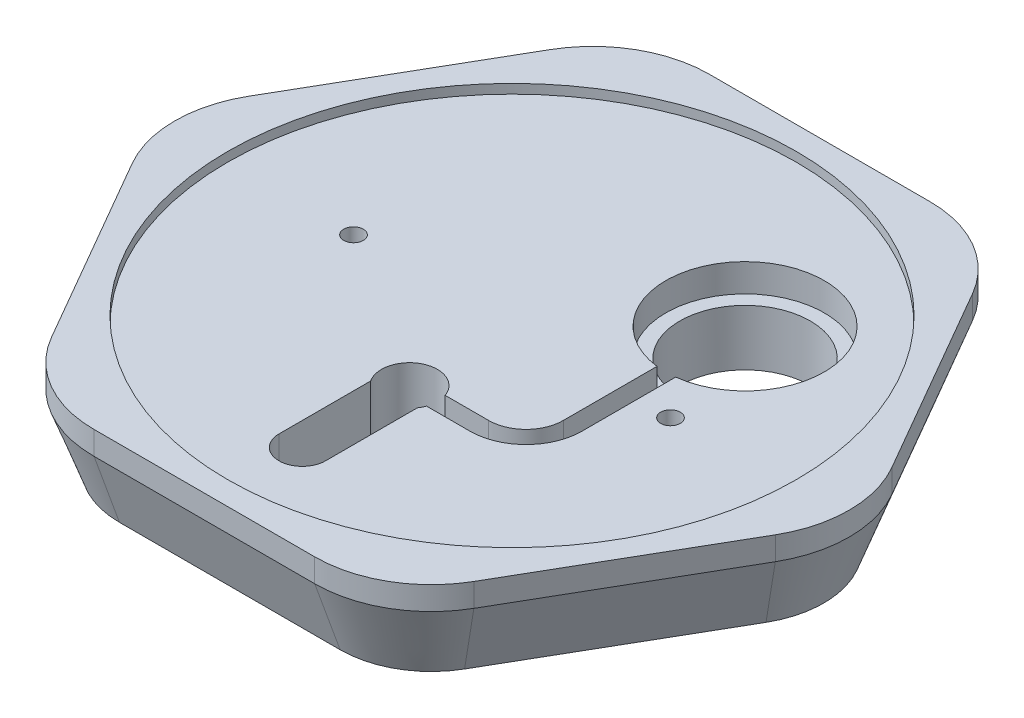
SolidWorks part; units mm, degrees
ref_plane "Front Plane" through (0, 0, 0) normal (0, 0, 1) x (1, 0, 0)
ref_plane "Top Plane" through (0, 0, 0) normal (0, 1, 0) x (1, 0, 0)
ref_plane "Right Plane" through (0, 0, 0) normal (1, 0, 0) x (0, 0, -1)
sketch "Sketch1" plane through (0, 0, 0) normal (0, 1, 0) x (1, 0, 0)
  line L1 (68.9934, 12.5) -> (45.322, 53.5)
  line L2 (23.6714, 66) -> (-23.6714, 66)
  line L3 (-45.322, 53.5) -> (-68.9934, 12.5)
  line L4 (-68.9934, -12.5) -> (-45.322, -53.5)
  line L5 (-23.6714, -66) -> (23.6714, -66)
  line L6 (45.322, -53.5) -> (68.9934, -12.5)
  circle A0 centre (0, 0) radius 66 construction
  arc A1 (-68.9934, 12.5) -> (-68.9934, -12.5) centre (-47.3427, 0) ccw
  arc A2 (-45.322, -53.5) -> (-23.6714, -66) centre (-23.6714, -41) ccw
  arc A3 (23.6714, -66) -> (45.322, -53.5) centre (23.6714, -41) ccw
  arc A4 (68.9934, -12.5) -> (68.9934, 12.5) centre (47.3427, 0) ccw
  arc A5 (45.322, 53.5) -> (23.6714, 66) centre (23.6714, 41) ccw
  arc A6 (-23.6714, 66) -> (-45.322, 53.5) centre (-23.6714, 41) ccw
  dimension "D2" = 25
  dimension "D1" = 132
extrude "Boss-Extrude1" add sketch "Sketch1" along normal blind 5
sketch "Sketch2" plane through (0, 0, 0) normal (0, -1, 0) x (1, 0, 0)
  line L6 (-68.9934, -12.5) -> (-45.322, -53.5)
  line L7 (-23.6714, -66) -> (23.6714, -66)
  line L8 (45.322, -53.5) -> (68.9934, -12.5)
  line L9 (68.9934, 12.5) -> (45.322, 53.5)
  line L10 (23.6714, 66) -> (-23.6714, 66)
  line L11 (-45.322, 53.5) -> (-68.9934, 12.5)
  line L12 (-68.9934, -12.5) -> (-45.322, -53.5)
  line L13 (-23.6714, -66) -> (23.6714, -66)
  line L14 (45.322, -53.5) -> (68.9934, -12.5)
  line L15 (68.9934, 12.5) -> (45.322, 53.5)
  line L16 (23.6714, 66) -> (-23.6714, 66)
  line L17 (-45.322, 53.5) -> (-68.9934, 12.5)
  arc A6 (-68.9934, 12.5) -> (-68.9934, -12.5) centre (-47.3427, 0) ccw
  arc A7 (-45.322, -53.5) -> (-23.6714, -66) centre (-23.6714, -41) ccw
  arc A8 (23.6714, -66) -> (45.322, -53.5) centre (23.6714, -41) ccw
  arc A9 (68.9934, -12.5) -> (68.9934, 12.5) centre (47.3427, 0) ccw
  arc A10 (45.322, 53.5) -> (23.6714, 66) centre (23.6714, 41) ccw
  arc A11 (-23.6714, 66) -> (-45.322, 53.5) centre (-23.6714, 41) ccw
  arc A12 (-68.9934, 12.5) -> (-68.9934, -12.5) centre (-47.3427, 0) ccw
  arc A13 (-45.322, -53.5) -> (-23.6714, -66) centre (-23.6714, -41) ccw
  arc A14 (23.6714, -66) -> (45.322, -53.5) centre (23.6714, -41) ccw
  arc A15 (68.9934, -12.5) -> (68.9934, 12.5) centre (47.3427, 0) ccw
  arc A16 (45.322, 53.5) -> (23.6714, 66) centre (23.6714, 41) ccw
  arc A17 (-23.6714, 66) -> (-45.322, 53.5) centre (-23.6714, 41) ccw
  dimension "D1" = 0
extrude "Boss-Extrude2" add sketch "Sketch2" along normal blind 15 draft 20
sketch "Sketch3" plane through (0, 5, 0) normal (0, 1, 0) x (1, 0, 0)
  circle A0 centre (0, 0) radius 61
  dimension "D1" = 122
extrude "Cut-Extrude1" cut sketch "Sketch3" against normal blind 2
sketch "Sketch4" plane through (0, 3, 0) normal (0, 1, 0) x (1, 0, 0)
  circle A0 centre (25, 25) radius 17
  dimension "D2" = 34
  dimension "D1" = 25
  dimension "D3" = 25
extrude "Cut-Extrude2" cut sketch "Sketch4" against normal blind 6
sketch "Sketch7" plane through (0, -3, 0) normal (0, 1, 0) x (1, 0, 0)
  circle A0 centre (25, 25) radius 17 construction
  circle A1 centre (25, 25) radius 17 construction
  circle A2 centre (25, 25) radius 14
  dimension "D1" = 28
extrude "Cut-Extrude3" cut sketch "Sketch7" against normal up to next
sketch "Sketch8" plane through (0, -15, 0) normal (0, -1, 0) x (-1, 0, 0)
  circle A0 centre (0, 0) radius 12.75
  dimension "D1" = 25.5
extrude "Cut-Extrude4" cut sketch "Sketch8" against normal offset from surface (16 mm away) 2 up to face at (25, 3, -8)
sketch "Sketch9" plane through (0, 3, 0) normal (0, 1, 0) x (1, 0, 0)
  circle A0 centre (34, 0) radius 2.1
  circle A1 centre (-34, 0) radius 2.1
  dimension "D1" = 4.2
  dimension "D2" = 4.2
  dimension "D3" = 34
  dimension "D4" = 34
extrude "Cut-Extrude5" cut sketch "Sketch9" against normal blind 20
sketch "Sketch12" plane through (0, 0, -66) normal (0, 0, -1) x (-1, 0, 0)
  circle A0 centre (0, -7) radius 4.1
  dimension "D1" = 8.2
  dimension "D2" = 7
extrude "Cut-Extrude7" cut sketch "Sketch12" against normal blind 60
sketch "Sketch13" plane through (0, 0, -66) normal (0, 0, -1) x (-1, 0, 0)
  circle A2 centre (0, -7) radius 7.1
  circle A5 centre (0, -7) radius 4.1 construction
  circle A6 centre (0, -7) radius 4.1
  dimension "D1" = 14.2
extrude "Cut-Extrude8" cut sketch "Sketch13" against normal blind 18 contours A2
sketch "Sketch14" plane through (0, -15, 0) normal (0, -1, 0) x (-1, 0, 0)
  line L0 (0, 0) -> (0, 25) construction
  line L1 (-7.25, 28.5) -> (7.25, 28.5)
  line L2 (-7.25, 28.5) -> (-7.25, 21.5)
  line L3 (-7.25, 21.5) -> (7.25, 21.5)
  line L4 (7.25, 28.5) -> (7.25, 21.5)
  line L5 (-7.25, 28.5) -> (7.25, 21.5) construction
  line L6 (-7.25, 21.5) -> (7.25, 28.5) construction
  point P0 (0, 25)
  dimension "D1" = 14.5
  dimension "D2" = 7
  dimension "D3" = 25
extrude "Cut-Extrude9" cut sketch "Sketch14" against normal blind 16
sketch "Sketch15" plane through (0, -15, 0) normal (0, -1, 0) x (1, 0, 0)
  line L1 (-34, 4.1569) -> (-37.6, 2.0785)
  line L2 (-37.6, 2.0785) -> (-37.6, -2.0785)
  line L3 (-37.6, -2.0785) -> (-34, -4.1569)
  line L4 (-34, -4.1569) -> (-30.4, -2.0785)
  line L5 (-30.4, -2.0785) -> (-30.4, 2.0785)
  line L6 (-30.4, 2.0785) -> (-34, 4.1569)
  line L7 (34, 4.1569) -> (30.4, 2.0785)
  line L8 (30.4, 2.0785) -> (30.4, -2.0785)
  line L9 (30.4, -2.0785) -> (34, -4.1569)
  line L10 (34, -4.1569) -> (37.6, -2.0785)
  line L11 (37.6, -2.0785) -> (37.6, 2.0785)
  line L12 (37.6, 2.0785) -> (34, 4.1569)
  circle A0 centre (-34, 0) radius 2.1 construction
  circle A1 centre (34, 0) radius 2.1 construction
  circle A2 centre (-34, 0) radius 2.1
  circle A3 centre (34, 0) radius 2.1
  circle A6 centre (-34, 0) radius 3.6 construction
  circle A7 centre (34, 0) radius 3.6 construction
  dimension "D1" = 7.2
  dimension "D2" = 7.2
extrude "Cut-Extrude10" cut sketch "Sketch15" against normal blind 5
sketch "Sketch16" plane through (0, 3, 0) normal (0, 1, 0) x (1, 0, 0)
  circle A0 centre (0, -22) radius 6
  dimension "D2" = 12
  dimension "D1" = 22
extrude "Cut-Extrude11" cut sketch "Sketch16" against normal up to next
sketch "Sketch17" plane through (0, 3, 0) normal (0, 1, 0) x (1, 0, 0)
  line L0 (25, 25) -> (25, -12)
  line L1 (15, -22) -> (0, -22)
  line L2 (23, 25) -> (23, -12)
  line L3 (15, -20) -> (0, -20)
  line L4 (27, 25) -> (27, -12)
  line L5 (15, -24) -> (0, -24)
  line L6 (23, 25) -> (27, 25)
  line L7 (0, -24) -> (0, -20)
  circle A0 centre (25, 25) radius 17 construction
  circle A1 centre (25, 25) radius 17
  circle A2 centre (0, -22) radius 6 construction
  circle A3 centre (0, -22) radius 6
  arc A4 (25, -12) -> (15, -22) centre (15, -12) cw
  arc A5 (23, -12) -> (15, -20) centre (15, -12) cw
  arc A6 (27, -12) -> (15, -24) centre (15, -12) cw
  circle M6 centre (0, -22) radius 6
  circle M10 centre (25, 25) radius 17
  dimension "D1" = 10
  dimension "D2" = 2
  dimension "D3" = 2
extrude "Cut-Extrude12" cut sketch "Sketch17" against normal blind 12 contours L2 A5 L3 L1 A4 L0 M6 M10 | A6 L4 L0 A4 L1 L5 M10 M6 | L6 L2 L0 M10 | L6 L0 L4 M10
sketch "Sketch18" plane through (0, 3, 0) normal (0, 1, 0) x (1, 0, 0)
  line L0 (0, -25) -> (0, -45) construction
  line L1 (5, -25) -> (5, -45)
  line L2 (-5, -25) -> (-5, -45)
  arc A0 (5, -25) -> (-5, -25) centre (0, -25) ccw
  arc A1 (-5, -45) -> (5, -45) centre (0, -45) ccw
  point P2 (0, -35)
  dimension "D1" = 5
  dimension "D2" = 45
  dimension "D3" = 20
extrude "Cut-Extrude13" cut sketch "Sketch18" against normal blind 10
